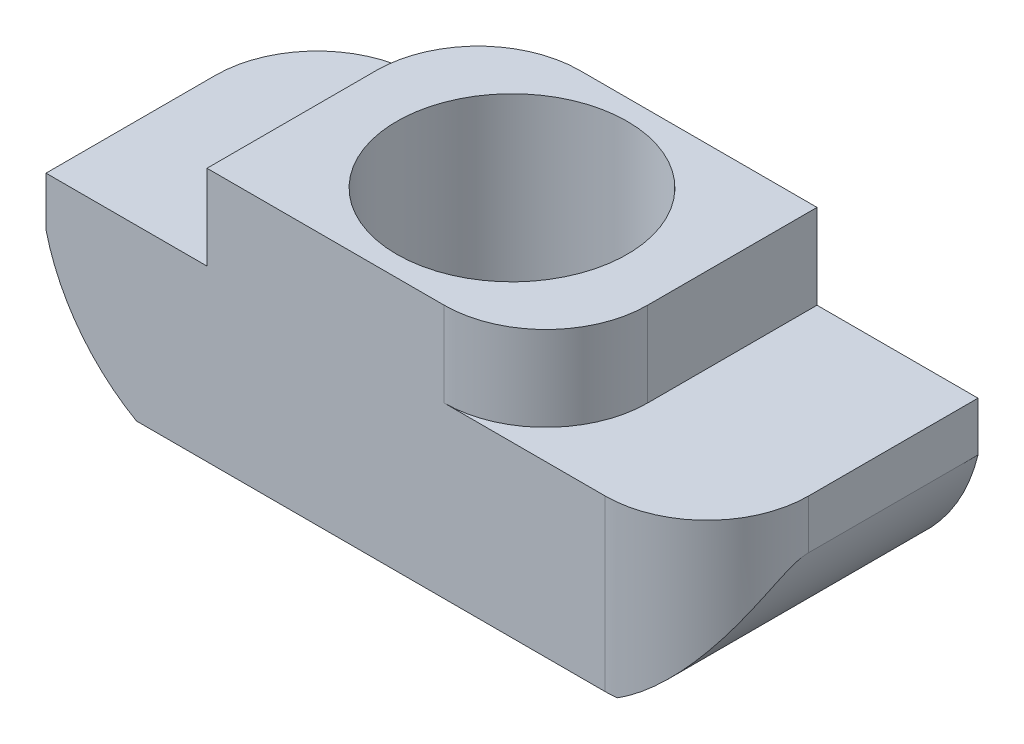
SolidWorks part; units mm, degrees
ref_plane "前视基准面" through (0, 0, 0) normal (0, 0, 1) x (1, 0, 0)
ref_plane "上视基准面" through (0, 0, 0) normal (0, 1, 0) x (1, 0, 0)
ref_plane "右视基准面" through (0, 0, 0) normal (1, 0, 0) x (0, 0, -1)
sketch "草图1" plane through (0, 0, 0) normal (0, 0, 1) x (1, 0, 0)
  line B0 (16.8321, -5) -> (2.6679, -5)
  line B1 (19.5, 0) -> (19.5, -1.45)
  line B2 (19.5, 0) -> (0, 0)
  line B3 (0, 0) -> (0, -1.45)
  arc B4 (16.8321, -5) -> (19.5, -1.45) centre (14.0298, -0.1166) ccw
  arc B5 (0, -1.45) -> (2.6679, -5) centre (5.4702, -0.1166) ccw
sketch_block_instance "A$C704C57A6-1"
sketch_block "A$C704C57A6"
extrude "凸台-拉伸1" add sketch "草图1" along normal mid plane 8
sketch "草图3" plane through (0, 0, 0) normal (0, 0, 1) x (1, 0, 0)
  line L0 (9.75, 0) -> (9.75, 4.4674) construction
  line L1 (19.5, 0) -> (0, 0) construction
  line B0 (14.75, 0) -> (4.75, 0)
  line B1 (14.75, 0) -> (14.75, 2.5)
  line B2 (14.75, 2.5) -> (4.75, 2.5)
  line B3 (4.75, 0) -> (4.75, 2.5)
sketch_block_instance "A$C373359D1-1"
sketch_block "A$C373359D1"
extrude "凸台-拉伸2" add sketch "草图3" along normal mid plane 8
fillet "圆角1" radius 3 4 edges at (19.5, -0.725, 4) (0, -0.725, -4)
sketch "草图5" plane through (0, 2.5, 0) normal (0, 1, 0) x (1, 0, 0)
  line L0 (0, -4) -> (0, 1) construction
  point P0 (9.75, 0)
  dimension "D1" = 9.75
hole_wizard "M8 螺纹孔1" positions "3D草图1" profile "草图6" tap size "M8" standard "Iso"
sketch3d "3D草图1"
  point P0 (9.75, 2.5, 0)
sketch "草图6" plane through (9.75, 2.5, 0) normal (1, 0, 0) x (0, 0, 1)
  line L0 (0, 0) -> (0, 21.7929)
  line L1 (0, 21.7929) -> (3.4, 19.75)
  line L2 (3.4, 19.75) -> (3.4, 0)
  line L5 (3.4, 0) -> (0, 0)
  line L10 (0, 21.7929) -> (-3.4, 19.75) construction
  line L11 (0, -6.35) -> (0, 107.95) construction
  dimension "螺纹孔钻头直径" = 6.8
  dimension "螺纹孔钻头深度" = 19.75
  dimension "导头角度" = 118
cosmetic thread "孔螺蚊线1"
